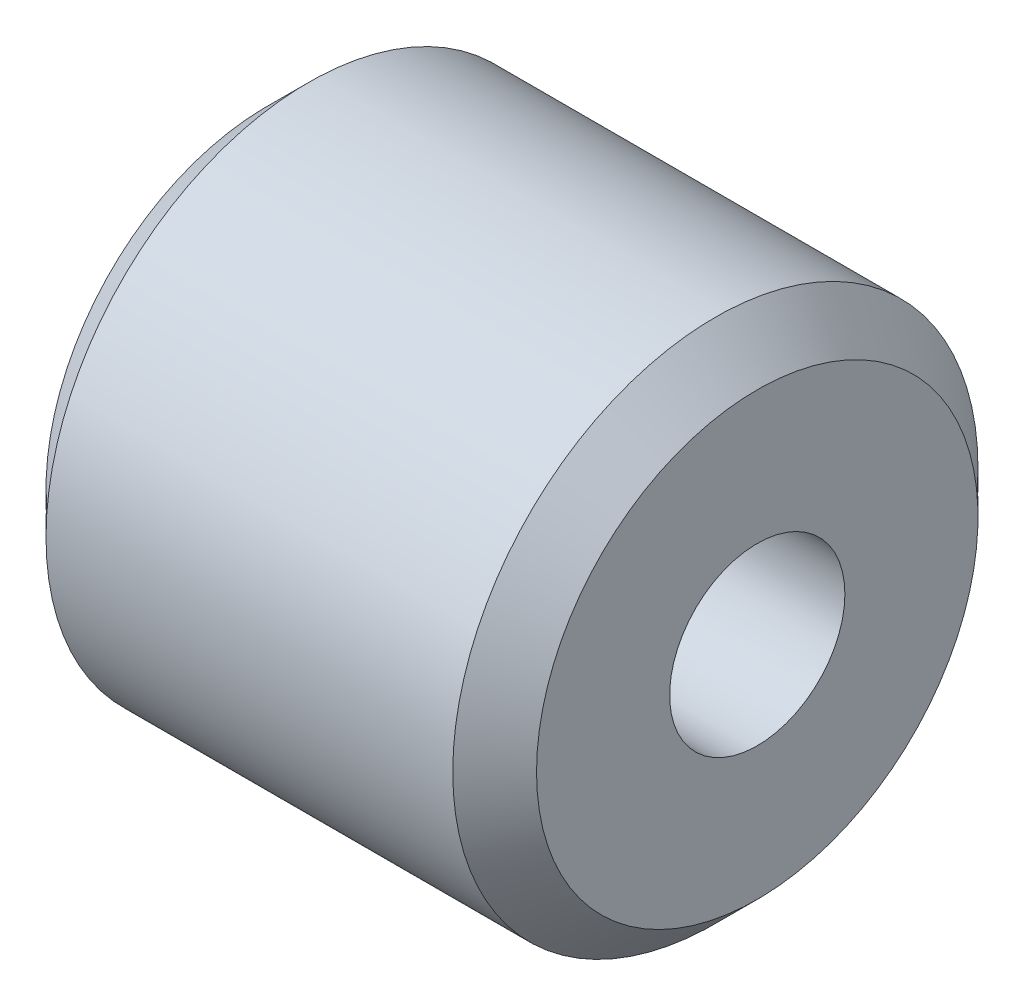
SolidWorks part; units mm, degrees
ref_plane "Front Plane" through (0, 0, 0) normal (0, 0, 1) x (1, 0, 0)
ref_plane "Top Plane" through (0, 0, 0) normal (0, 1, 0) x (1, 0, 0)
ref_plane "Right Plane" through (0, 0, 0) normal (1, 0, 0) x (0, 0, -1)
sketch "Sketch1" plane through (0, 0, 0) normal (1, 0, 0) x (0, 0, -1)
  circle A0 centre (0, 0) radius 1.59
  circle A1 centre (0, 0) radius 4.765
  dimension "D1" = 3.18
  dimension "D2" = 9.53
extrude "Boss-Extrude1" add sketch "Sketch1" along normal mid plane 8.9
chamfer "Chamfer2" distance 0.76 angle 45 2 edges at (-4.45, 0, -4.765) (4.45, 0, -4.765)
